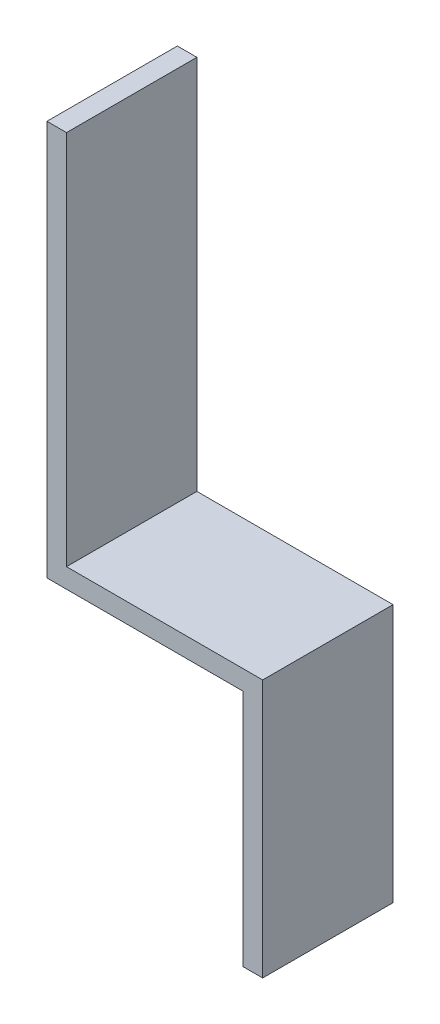
SolidWorks part; units mm, degrees
ref_plane "Front Plane" through (0, 0, 0) normal (0, 0, 1) x (1, 0, 0)
ref_plane "Top Plane" through (0, 0, 0) normal (0, 1, 0) x (1, 0, 0)
ref_plane "Right Plane" through (0, 0, 0) normal (1, 0, 0) x (0, 0, -1)
sketch "Sketch1" plane through (0, 0, 0) normal (0, 0, 1) x (1, 0, 0)
  line L7 (-3, -15.1097) -> (-3, -51.7012)
  line L10 (0, -12.1097) -> (0, -51.7012)
  line L11 (-3, -51.7012) -> (0, -51.7012)
  line L12 (-33.0845, -15.1097) -> (-3, -15.1097)
  line L14 (0, -12.1097) -> (-30.0845, -12.1097)
  line L15 (-30.0845, -12.1097) -> (-30.0845, 45.5504)
  line L16 (-30.0845, 45.5504) -> (-33.0845, 45.5504)
  line L17 (-33.0845, 45.5504) -> (-33.0845, -15.1097)
  dimension "D1" = 3
  dimension "D2" = 3
  dimension "D3" = 30.0845
  dimension "D4" = 39.5915
  dimension "D5" = 3
  dimension "D6" = 60.6601
extrude "Boss-Extrude1" add sketch "Sketch1" along normal blind 20
